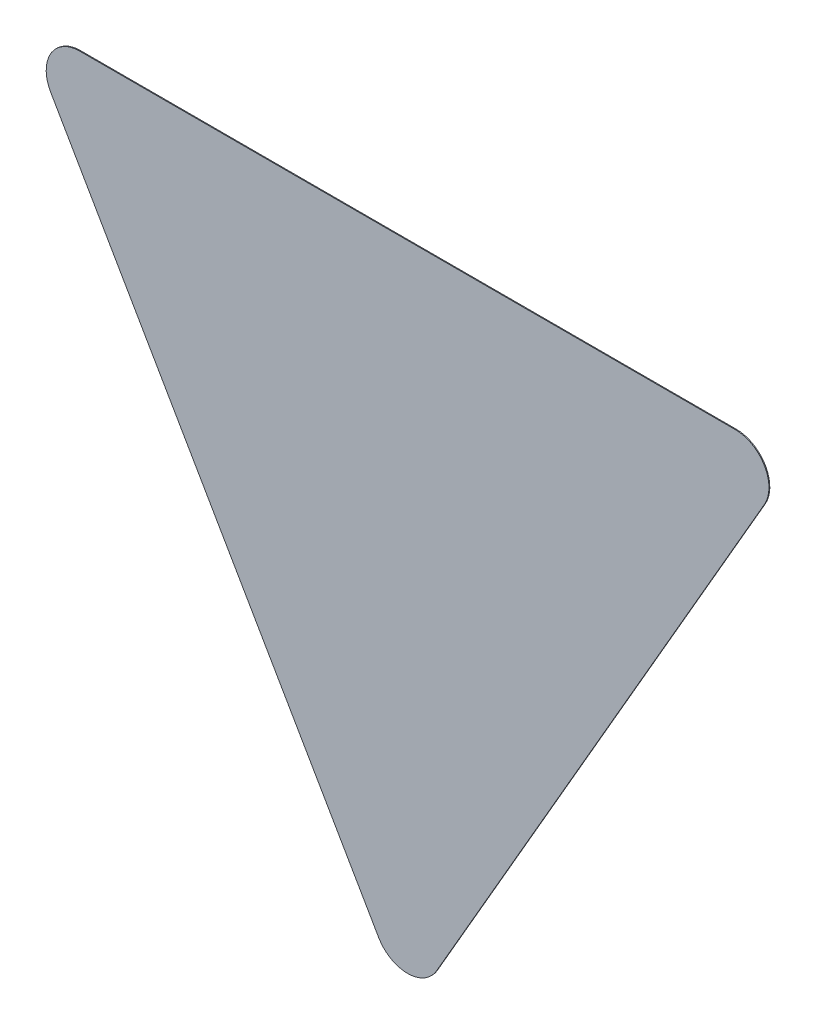
SolidWorks part; units mm, degrees
ref_plane "Front Plane" through (0, 0, 0) normal (0, 0, 1) x (1, 0, 0)
ref_plane "Top Plane" through (0, 0, 0) normal (0, 1, 0) x (1, 0, 0)
ref_plane "Right Plane" through (0, 0, 0) normal (1, 0, 0) x (0, 0, -1)
sketch "Sketch1" plane through (0, 0, 0) normal (0, 0, 1) x (1, 0, 0)
  line L14 (0, 25) -> (0, -25) construction
  line L49 (0, 25) -> (-24.5374, 25)
  line L50 (0, 25) -> (24.5374, 25)
  line L51 (-26.7024, 21.25) -> (-2.1651, -21.25)
  line L56 (2.1651, -21.25) -> (26.7024, 21.25)
  arc A0 (-2.1651, -21.25) -> (2.1651, -21.25) centre (0, -20) ccw
  arc A1 (26.7024, 21.25) -> (24.5374, 25) centre (24.5374, 22.5) ccw
  arc A2 (-26.7024, 21.25) -> (-24.5374, 25) centre (-24.5374, 22.5) cw
  point P0 (0, 0)
  point P10 (28.8675, 25)
  point P13 (-28.8675, 25)
  dimension "D3" = 2.5
  dimension "D1" = 50
  dimension "D2" = 25
  dimension "D20" = 28.8675
  dimension "D21" = 28.8675
  dimension "D22" = 25
extrude "Boss-Extrude1" add sketch "Sketch1" along normal blind 0.065
